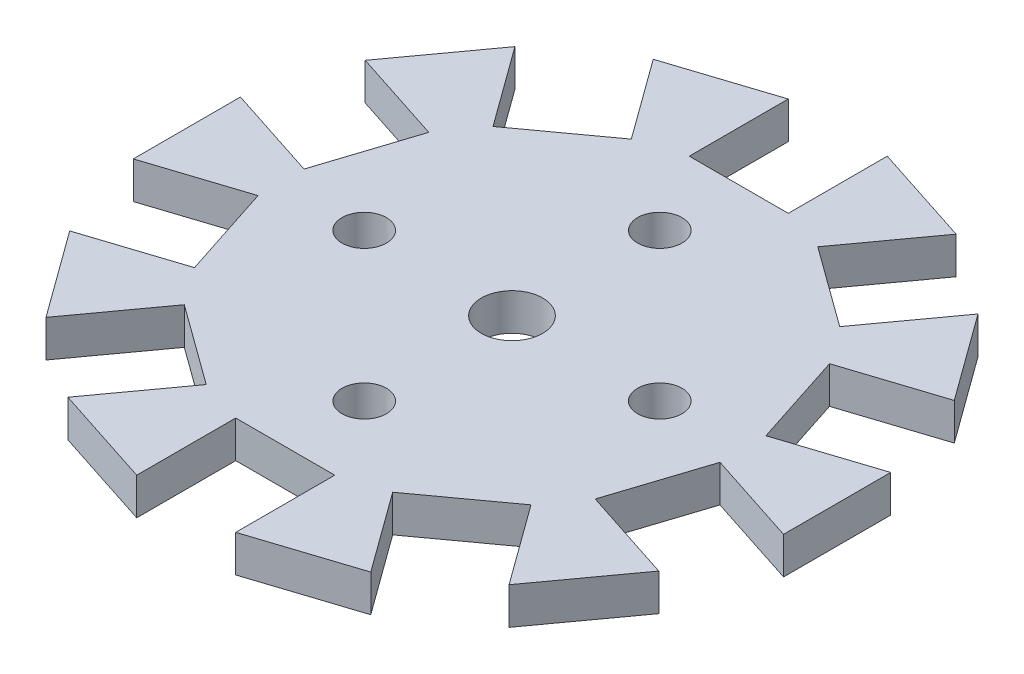
SolidWorks part; units mm, degrees
ref_plane "Front Plane" through (0, 0, 0) normal (0, 0, 1) x (1, 0, 0)
ref_plane "Top Plane" through (0, 0, 0) normal (0, 1, 0) x (1, 0, 0)
ref_plane "Right Plane" through (0, 0, 0) normal (1, 0, 0) x (0, 0, -1)
sketch "Sketch1" plane through (0, 0, 0) normal (0, 1, 0) x (1, 0, 0)
  line L1 (0, 23.1322) -> (-13.5967, 18.7143)
  line L2 (-13.5967, 18.7143) -> (-22, 7.1482)
  line L3 (-22, 7.1482) -> (-22, -7.1482)
  line L4 (-22, -7.1482) -> (-13.5967, -18.7143)
  line L5 (-13.5967, -18.7143) -> (0, -23.1322)
  line L6 (0, -23.1322) -> (13.5967, -18.7143)
  line L7 (13.5967, -18.7143) -> (22, -7.1482)
  line L8 (22, -7.1482) -> (22, 7.1482)
  line L9 (22, 7.1482) -> (13.5967, 18.7143)
  line L10 (13.5967, 18.7143) -> (0, 23.1322)
  circle A0 centre (0, 0) radius 22 construction
  dimension "D1" = 44
extrude "Boss-Extrude1" add sketch "Sketch1" along normal blind 2.5
sketch "Sketch2" plane through (0, 2.5, 0) normal (0, 1, 0) x (1, 0, 0)
  line L0 (0, 23.1322) -> (-3.35, 22.0437)
  line L1 (0, 23.1322) -> (-13.5967, 18.7143) construction
  line L2 (-3.35, 22.0437) -> (-3.35, 15.3437)
  line L3 (-3.35, 15.3437) -> (3.35, 15.3437)
  line L4 (3.35, 15.3437) -> (3.35, 22.0437)
  line L5 (13.5967, 18.7143) -> (0, 23.1322) construction
  line L6 (3.35, 22.0437) -> (0, 23.1322)
  line L7 (11.729, 10.4442) -> (15.6672, 15.8646)
  line L8 (15.6672, 15.8646) -> (13.5967, 18.7143)
  line L9 (13.5967, 18.7143) -> (10.2467, 19.8028)
  line L10 (10.2467, 19.8028) -> (6.3086, 14.3824)
  line L11 (6.3086, 14.3824) -> (11.729, 10.4442)
  line L12 (15.6279, 1.5554) -> (22, 3.6258)
  line L13 (22, 3.6258) -> (22, 7.1482)
  line L14 (22, 7.1482) -> (19.9296, 9.9979)
  line L15 (19.9296, 9.9979) -> (13.5575, 7.9275)
  line L16 (13.5575, 7.9275) -> (15.6279, 1.5554)
  line L17 (13.5575, -7.9275) -> (19.9296, -9.9979)
  line L18 (19.9296, -9.9979) -> (22, -7.1482)
  line L19 (22, -7.1482) -> (22, -3.6258)
  line L20 (22, -3.6258) -> (15.6279, -1.5554)
  line L21 (15.6279, -1.5554) -> (13.5575, -7.9275)
  line L22 (6.3086, -14.3824) -> (10.2467, -19.8028)
  line L23 (10.2467, -19.8028) -> (13.5967, -18.7143)
  line L24 (13.5967, -18.7143) -> (15.6672, -15.8646)
  line L25 (15.6672, -15.8646) -> (11.729, -10.4442)
  line L26 (11.729, -10.4442) -> (6.3086, -14.3824)
  line L27 (-3.35, -15.3437) -> (-3.35, -22.0437)
  line L28 (-3.35, -22.0437) -> (0, -23.1322)
  line L29 (0, -23.1322) -> (3.35, -22.0437)
  line L30 (3.35, -22.0437) -> (3.35, -15.3437)
  line L31 (3.35, -15.3437) -> (-3.35, -15.3437)
  line L32 (-11.729, -10.4442) -> (-15.6672, -15.8646)
  line L33 (-15.6672, -15.8646) -> (-13.5967, -18.7143)
  line L34 (-13.5967, -18.7143) -> (-10.2467, -19.8028)
  line L35 (-10.2467, -19.8028) -> (-6.3086, -14.3824)
  line L36 (-6.3086, -14.3824) -> (-11.729, -10.4442)
  line L37 (-15.6279, -1.5554) -> (-22, -3.6258)
  line L38 (-22, -3.6258) -> (-22, -7.1482)
  line L39 (-22, -7.1482) -> (-19.9296, -9.9979)
  line L40 (-19.9296, -9.9979) -> (-13.5575, -7.9275)
  line L41 (-13.5575, -7.9275) -> (-15.6279, -1.5554)
  line L42 (-13.5575, 7.9275) -> (-19.9296, 9.9979)
  line L43 (-19.9296, 9.9979) -> (-22, 7.1482)
  line L44 (-22, 7.1482) -> (-22, 3.6258)
  line L45 (-22, 3.6258) -> (-15.6279, 1.5554)
  line L46 (-15.6279, 1.5554) -> (-13.5575, 7.9275)
  line L47 (-6.3086, 14.3824) -> (-10.2467, 19.8028)
  line L48 (-10.2467, 19.8028) -> (-13.5967, 18.7143)
  line L49 (-13.5967, 18.7143) -> (-15.6672, 15.8646)
  line L50 (-15.6672, 15.8646) -> (-11.729, 10.4442)
  line L51 (-11.729, 10.4442) -> (-6.3086, 14.3824)
  point P5 (0, 15.3437)
  point P59 (0, 0)
  dimension "D1" = 6.7
  dimension "D2" = 6.7
  dimension "D3" = 10
extrude "Cut-Extrude1" cut sketch "Sketch2" against normal up to surface (2.5 mm away) up to face at (0, 0, 0)
sketch "Sketch7" plane through (0, 2.5, 0) normal (0, 1, 0) x (1, 0, 0)
  circle A0 centre (0, 0) radius 10 construction
  circle A1 centre (0, 10) radius 1.5
  circle A2 centre (10, 0) radius 1.5
  circle A3 centre (0, -10) radius 1.5
  circle A4 centre (-10, 0) radius 1.5
  dimension "D1" = 20
  dimension "D2" = 3
extrude "Cut-Extrude3" cut sketch "Sketch7" against normal up to surface (2.5 mm away) up to face at (0, 0, 0)
sketch "Sketch10" plane through (0, 2.5, 0) normal (0, 1, 0) x (1, 0, 0)
  circle A0 centre (0, 0) radius 2.075
  dimension "D1" = 4.15
extrude "Cut-Extrude6" cut sketch "Sketch10" against normal up to surface (2.5 mm away) up to face at (0, 0, -8.5)
sketch "Sketch4" plane through (0, 2.5, 0) normal (0, 1, 0) x (1, 0, 0)
  line L0 (-3.35, 15.3437) -> (3.35, 15.3437) construction
  line L1 (-4.55, 18.9437) -> (4.55, 18.9437)
  line L2 (-4.55, 18.9437) -> (-4.55, 20.5437)
  line L3 (-4.55, 20.5437) -> (4.55, 20.5437)
  line L4 (4.55, 18.9437) -> (4.55, 20.5437)
  line L5 (-4.55, 18.9437) -> (4.55, 20.5437) construction
  line L6 (-4.55, 20.5437) -> (4.55, 18.9437) construction
  line L7 (7.4538, 18.0002) -> (8.3942, 19.2946)
  line L8 (7.4538, 18.0002) -> (14.8158, 12.6513)
  line L9 (14.8158, 12.6513) -> (15.7563, 13.9458)
  line L10 (8.3942, 19.2946) -> (15.7563, 13.9458)
  line L11 (16.6105, 10.1812) -> (18.1322, 10.6757)
  line L12 (16.6105, 10.1812) -> (19.4225, 1.5266)
  line L13 (19.4225, 1.5266) -> (20.9442, 2.021)
  line L14 (18.1322, 10.6757) -> (20.9442, 2.021)
  line L15 (19.4225, -1.5266) -> (20.9442, -2.021)
  line L16 (19.4225, -1.5266) -> (16.6105, -10.1812)
  line L17 (16.6105, -10.1812) -> (18.1322, -10.6757)
  line L18 (20.9442, -2.021) -> (18.1322, -10.6757)
  line L19 (14.8158, -12.6513) -> (15.7563, -13.9458)
  line L20 (14.8158, -12.6513) -> (7.4538, -18.0002)
  line L21 (7.4538, -18.0002) -> (8.3942, -19.2946)
  line L22 (15.7563, -13.9458) -> (8.3942, -19.2946)
  line L23 (4.55, -18.9437) -> (4.55, -20.5437)
  line L24 (4.55, -18.9437) -> (-4.55, -18.9437)
  line L25 (-4.55, -18.9437) -> (-4.55, -20.5437)
  line L26 (4.55, -20.5437) -> (-4.55, -20.5437)
  line L27 (-7.4538, -18.0002) -> (-8.3942, -19.2946)
  line L28 (-7.4538, -18.0002) -> (-14.8158, -12.6513)
  line L29 (-14.8158, -12.6513) -> (-15.7563, -13.9458)
  line L30 (-8.3942, -19.2946) -> (-15.7563, -13.9458)
  line L31 (-16.6105, -10.1812) -> (-18.1322, -10.6757)
  line L32 (-16.6105, -10.1812) -> (-19.4225, -1.5266)
  line L33 (-19.4225, -1.5266) -> (-20.9442, -2.021)
  line L34 (-18.1322, -10.6757) -> (-20.9442, -2.021)
  line L35 (-19.4225, 1.5266) -> (-20.9442, 2.021)
  line L36 (-19.4225, 1.5266) -> (-16.6105, 10.1812)
  line L37 (-16.6105, 10.1812) -> (-18.1322, 10.6757)
  line L38 (-20.9442, 2.021) -> (-18.1322, 10.6757)
  line L39 (-14.8158, 12.6513) -> (-15.7563, 13.9458)
  line L40 (-14.8158, 12.6513) -> (-7.4538, 18.0002)
  line L41 (-7.4538, 18.0002) -> (-8.3942, 19.2946)
  line L42 (-15.7563, 13.9458) -> (-8.3942, 19.2946)
  point P0 (0, 19.7437)
  point P46 (0, 0)
  dimension "D1" = 9.1
  dimension "D2" = 1.6
  dimension "D3" = 4.4
  dimension "D4" = 10
extrude "Cut-Extrude2" [suppressed] cut sketch "Sketch4" against normal blind 1.6
sketch "Sketch8" plane through (0, 0, 0) normal (0, -1, 0) x (1, 0, 0)
  circle A0 centre (0, 0) radius 13
  dimension "D1" = 26
extrude "Cut-Extrude4" [suppressed] cut sketch "Sketch8" against normal blind 1
sketch "Sketch9" plane through (0, 2.5, 0) normal (0, 1, 0) x (1, 0, 0)
  line L0 (0, 13.05) -> (0, -13.05) construction
  line L1 (3.5218, 10) -> (1.7609, 13.05)
  line L2 (1.7609, 13.05) -> (-1.7609, 13.05)
  line L3 (-1.7609, 13.05) -> (-3.5218, 10)
  line L4 (-3.5218, 10) -> (-1.7609, 6.95)
  line L5 (-1.7609, 6.95) -> (1.7609, 6.95)
  line L6 (1.7609, 6.95) -> (3.5218, 10)
  line L7 (3.5218, -10) -> (1.7609, -6.95)
  line L8 (1.7609, -6.95) -> (-1.7609, -6.95)
  line L9 (-1.7609, -6.95) -> (-3.5218, -10)
  line L10 (-3.5218, -10) -> (-1.7609, -13.05)
  line L11 (-1.7609, -13.05) -> (1.7609, -13.05)
  line L12 (1.7609, -13.05) -> (3.5218, -10)
  line L13 (13.5218, 0) -> (11.7609, 3.05)
  line L14 (11.7609, 3.05) -> (8.2391, 3.05)
  line L15 (8.2391, 3.05) -> (6.4782, 0)
  line L16 (6.4782, 0) -> (8.2391, -3.05)
  line L17 (8.2391, -3.05) -> (11.7609, -3.05)
  line L18 (11.7609, -3.05) -> (13.5218, 0)
  line L19 (-6.4782, 0) -> (-8.2391, 3.05)
  line L20 (-8.2391, 3.05) -> (-11.7609, 3.05)
  line L21 (-11.7609, 3.05) -> (-13.5218, 0)
  line L22 (-13.5218, 0) -> (-11.7609, -3.05)
  line L23 (-11.7609, -3.05) -> (-8.2391, -3.05)
  line L24 (-8.2391, -3.05) -> (-6.4782, 0)
  circle A4 centre (0, 10) radius 3.05 construction
  circle A5 centre (0, -10) radius 3.05 construction
  circle A6 centre (10, 0) radius 3.05 construction
  circle A7 centre (-10, 0) radius 3.05 construction
  dimension "D1" = 6.1
extrude "Cut-Extrude5" [suppressed] cut sketch "Sketch9" against normal blind 1
equation "\"E\"=10"
